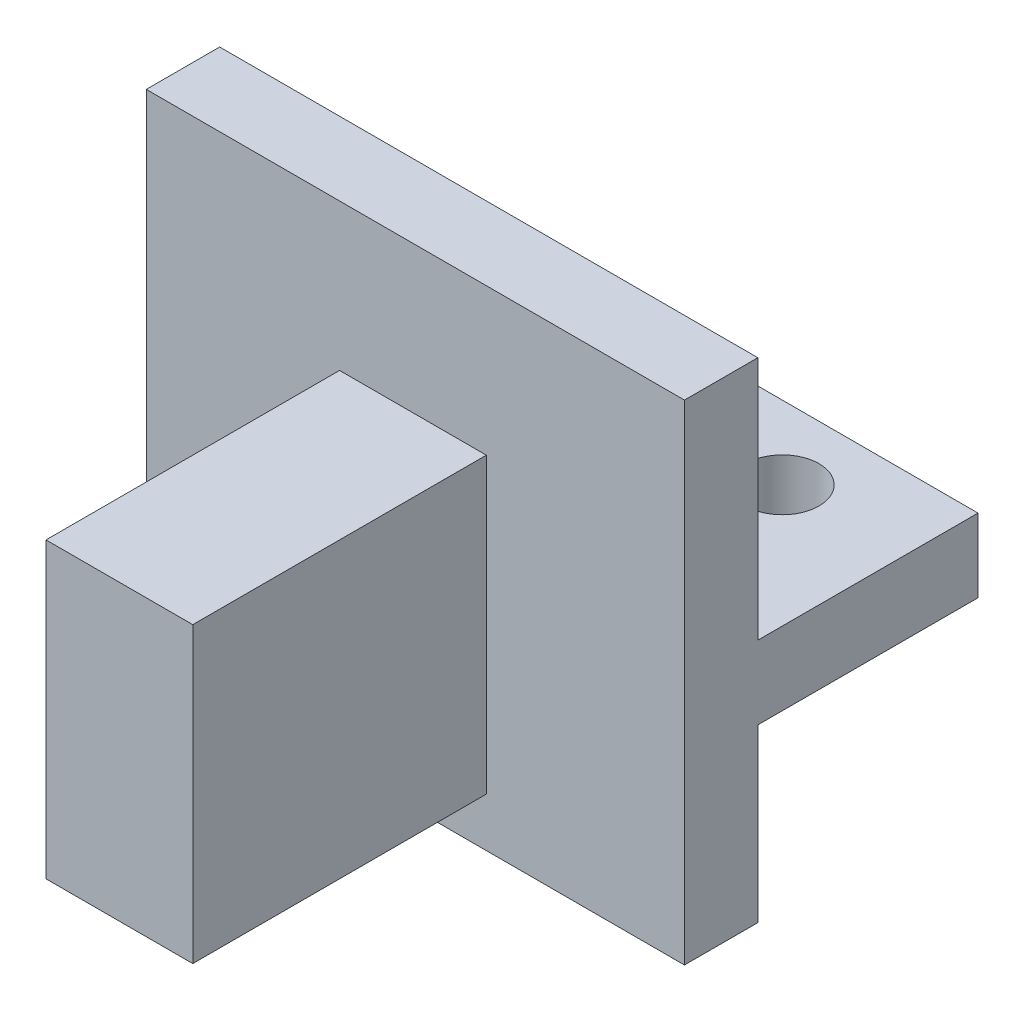
SolidWorks part; units mm, degrees
ref_plane "Plan de face" through (0, 0, 0) normal (0, 0, 1) x (1, 0, 0)
ref_plane "Plan de dessus" through (0, 0, 0) normal (0, 1, 0) x (1, 0, 0)
ref_plane "Plan de droite" through (0, 0, 0) normal (1, 0, 0) x (0, 0, -1)
sketch "Esquisse1" plane through (0, 0, 0) normal (0, 1, 0) x (1, 0, 0)
  line L0 (2.1093, 1.8062) -> (2.1093, -5.1938) construction
  line L1 (-8.8907, 1.8062) -> (13.1093, 1.8062)
  line L2 (-8.8907, 1.8062) -> (-8.8907, -5.1938)
  line L3 (-8.8907, -5.1938) -> (13.1093, -5.1938)
  line L4 (13.1093, 1.8062) -> (13.1093, -5.1938)
  circle A0 centre (-3.8907, -1.1938) radius 1.5
  circle A1 centre (8.1093, -1.1938) radius 1.5
  dimension "D3" = 6
  dimension "D4" = 3
  dimension "D1" = 22
  dimension "D2" = 7
  dimension "D5" = 4
extrude "Boss.-Extru.1" add sketch "Esquisse1" along normal blind 3
sketch "Esquisse4" plane through (0, 0, 5.1938) normal (0, 0, 1) x (1, 0, 0)
  line L1 (-8.8907, 3) -> (13.1093, 3)
  line L2 (-8.8907, 3) -> (-8.8907, 0)
  line L3 (-8.8907, 0) -> (13.1093, 0)
  line L4 (13.1093, 3) -> (13.1093, 0)
extrude "Boss.-Extru.2" add sketch "Esquisse4" along normal blind 5
sketch "Esquisse5" plane through (0, 3, 0) normal (0, 1, 0) x (1, 0, 0)
  line L0 (13.1093, -10.1938) -> (13.1093, 1.8062) construction
  line L1 (-8.8907, -10.1938) -> (13.1093, -10.1938)
  line L2 (-8.8907, -10.1938) -> (-8.8907, -7.1938)
  line L3 (-8.8907, -7.1938) -> (13.1093, -7.1938)
  line L4 (13.1093, -10.1938) -> (13.1093, -7.1938)
  dimension "D1" = 3
extrude "Boss.-Extru.3" add sketch "Esquisse5" along normal blind 10
sketch "Esquisse6" plane through (0, 0, 0) normal (0, -1, 0) x (1, 0, 0)
  line L0 (13.1093, 10.1938) -> (13.1093, -1.8062) construction
  line L1 (-8.8907, 10.1938) -> (13.1093, 10.1938)
  line L2 (-8.8907, 10.1938) -> (-8.8907, 7.1938)
  line L3 (-8.8907, 7.1938) -> (13.1093, 7.1938)
  line L4 (13.1093, 10.1938) -> (13.1093, 7.1938)
  dimension "D1" = 3
extrude "Boss.-Extru.4" add sketch "Esquisse6" along normal blind 7
sketch "Esquisse7" plane through (0, 0, 10.1938) normal (0, 0, 1) x (1, 0, 0)
  line L0 (1.9103, 13) -> (2.1093, -7) construction
  line L1 (-8.8907, 13) -> (13.1093, 13) construction
  line L2 (13.1093, -7) -> (-8.8907, -7) construction
  line L4 (5.0098, -5) -> (-0.9902, -5)
  line L5 (5.0098, -5) -> (5.0098, 7)
  line L6 (5.0098, 7) -> (-0.9902, 7)
  line L7 (-0.9902, -5) -> (-0.9902, 7)
  line L8 (5.0098, -5) -> (-0.9902, 7) construction
  line L9 (5.0098, 7) -> (-0.9902, -5) construction
  point P6 (2.0098, 1)
  dimension "D1" = 6
  dimension "D2" = 12
extrude "Boss.-Extru.5" add sketch "Esquisse7" along normal blind 12 contours L6 L7 L4 L5
